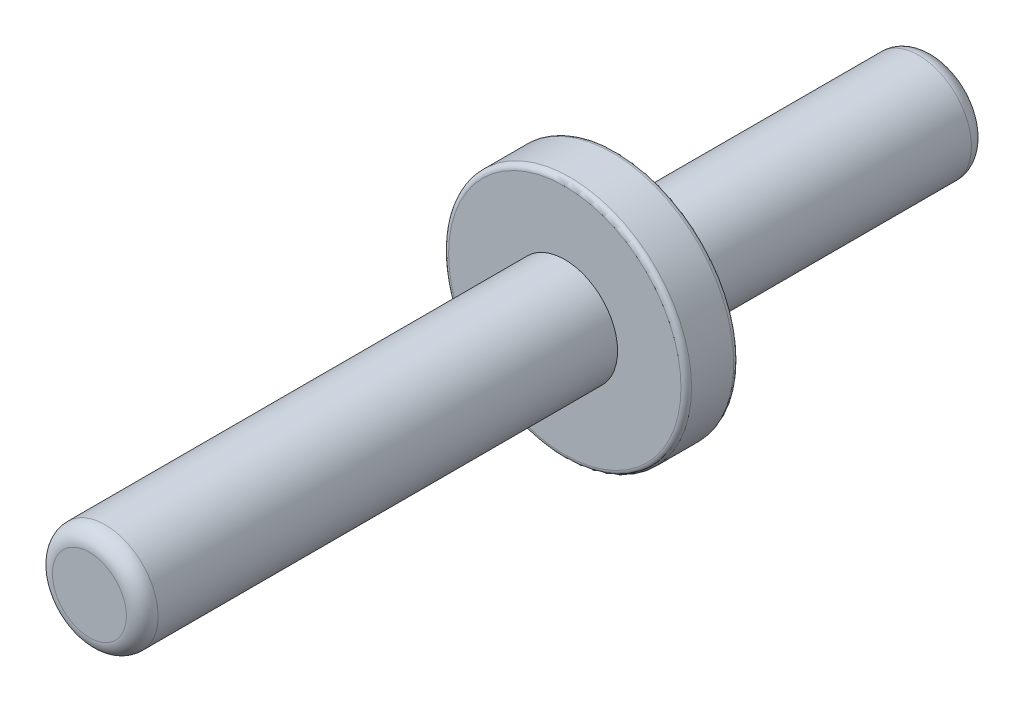
SolidWorks part; units mm, degrees
ref_plane "Front Plane" through (0, 0, 0) normal (0, 0, 1) x (1, 0, 0)
ref_plane "Top Plane" through (0, 0, 0) normal (0, 1, 0) x (1, 0, 0)
ref_plane "Right Plane" through (0, 0, 0) normal (1, 0, 0) x (0, 0, -1)
sketch "Sketch1" plane through (0, 0, 0) normal (0, 0, 1) x (1, 0, 0)
  circle A0 centre (0, 0) radius 2.3
  dimension "D1" = 4.6
extrude "Boss-Extrude1" add sketch "Sketch1" along normal blind 1
sketch "Sketch2" plane through (0, 0, 1) normal (0, 0, 1) x (1, 0, 0)
  circle A0 centre (0, 0) radius 1
  dimension "D1" = 2
extrude "Boss-Extrude2" add sketch "Sketch2" along normal blind 9
sketch "Sketch3" plane through (0, 0, 0) normal (0, 0, -1) x (-1, 0, 0)
  circle A0 centre (0, 0) radius 1
  dimension "D1" = 2
extrude "Boss-Extrude3" add sketch "Sketch3" along normal blind 6
fillet "Fillet2" radius 0.3 2 edges at (1, 0, 10) (-1, 0, -6)
fillet "Fillet3" radius 0.1 2 edges at (2.3, 0, 0) (2.3, 0, 1)
